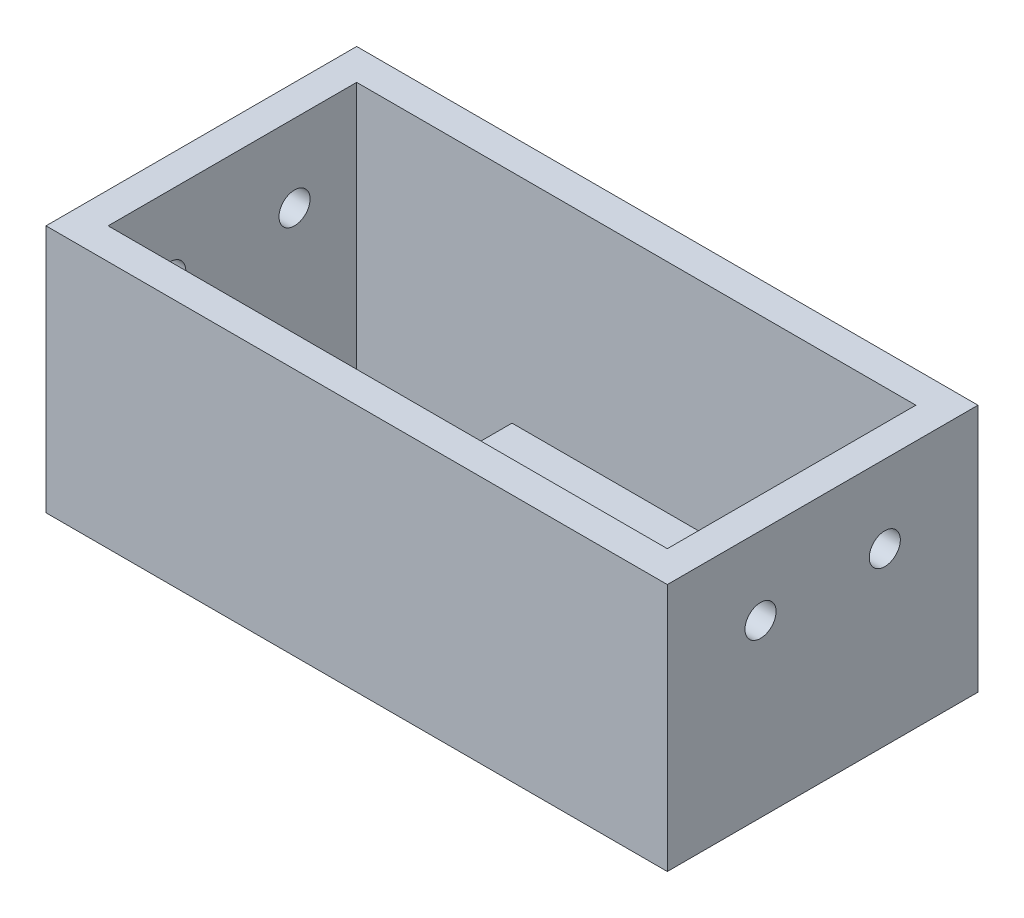
SolidWorks part; units mm, degrees
ref_plane "Front Plane" through (0, 0, 0) normal (0, 0, 1) x (1, 0, 0)
ref_plane "Top Plane" through (0, 0, 0) normal (0, 1, 0) x (1, 0, 0)
ref_plane "Right Plane" through (0, 0, 0) normal (1, 0, 0) x (0, 0, -1)
sketch "Sketch1" plane through (0, 0, 0) normal (0, 1, 0) x (1, 0, 0)
  line L0 (-50.3497, 0) -> (81.1189, 0) construction
  line L1 (-33.2284, 5) -> (-33.2284, 45)
  line L2 (-38.2284, 0) -> (61.7716, 0)
  line L3 (-38.2284, 0) -> (-38.2284, 50)
  line L4 (-38.2284, 50) -> (61.7716, 50)
  line L5 (61.7716, 0) -> (61.7716, 50)
  line L6 (-33.2284, 45) -> (56.7716, 45)
  line L7 (56.7716, 5) -> (56.7716, 45)
  line L8 (-33.2284, 5) -> (56.7716, 5)
  dimension "D1" = 100
  dimension "D2" = 50
  dimension "D3" = 5
extrude "Boss-Extrude1" add sketch "Sketch1" along normal blind 40
ref_plane "Plane1" through (0, 0, 0) normal (0, -1, 0) x (-1, 0, 0)
sketch "Sketch3" plane through (0, 0, 0) normal (0, -1, 0) x (-1, 0, 0)
  line L0 (-56.7716, 45) -> (33.2284, 45) construction
  line L1 (-31.7716, 45) -> (8.2284, 45)
  line L2 (-31.7716, 45) -> (-31.7716, 5)
  line L3 (-31.7716, 5) -> (8.2284, 5)
  line L4 (8.2284, 45) -> (8.2284, 5)
  line L5 (33.2284, 5) -> (-56.7716, 5) construction
  line L6 (38.2284, 50) -> (38.2284, 0) construction
  dimension "D1" = 40
  dimension "D2" = 30
extrude "Boss-Extrude2" add sketch "Sketch3" against normal blind 5
sketch "Sketch4" plane through (-38.2284, 0, 0) normal (-1, 0, 0) x (0, 0, 1)
  line L0 (-25, 0) -> (-25, 40) construction
  line L1 (-50, 0) -> (0, 0) construction
  line L2 (-50, 40) -> (0, 40) construction
  circle A0 centre (-35, 27.5) radius 2.5
  circle A1 centre (-15, 27.5) radius 2.5
  dimension "D1" = 5
  dimension "D2" = 5
  dimension "D3" = 20
  dimension "D4" = 10
  dimension "D5" = 12.5
extrude "Cut-Extrude1" cut sketch "Sketch4" against normal blind 116
